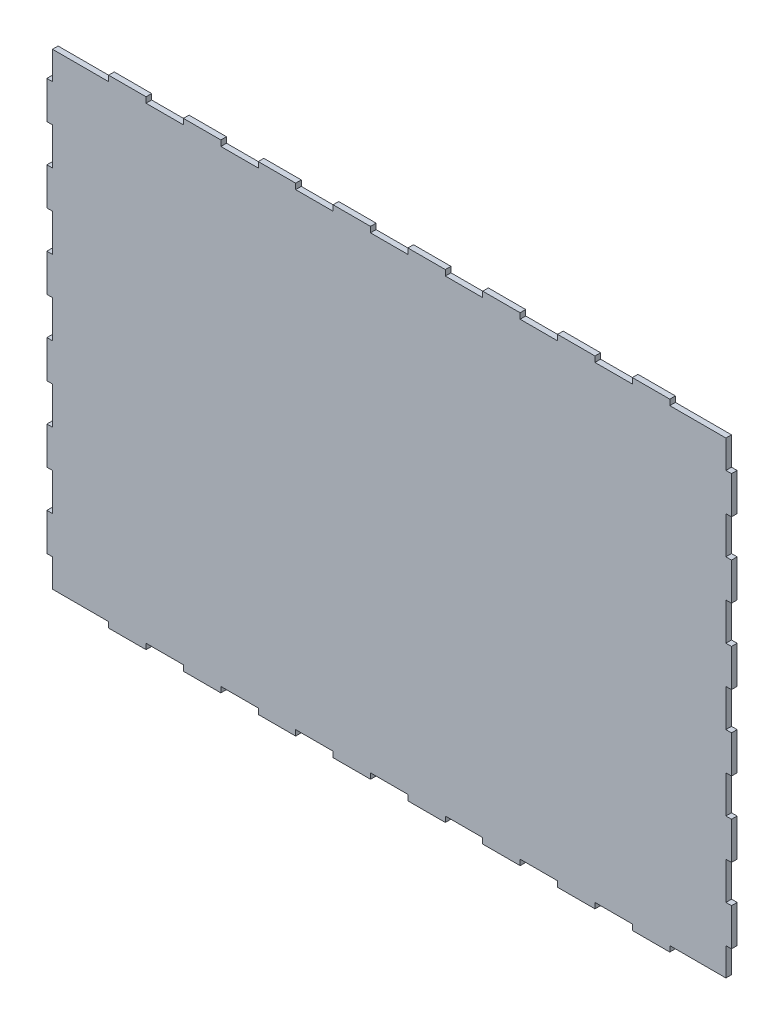
SolidWorks part; units mm, degrees
ref_plane "Front Plane" through (0, 0, 0) normal (0, 0, 1) x (1, 0, 0)
ref_plane "Top Plane" through (0, 0, 0) normal (0, 1, 0) x (1, 0, 0)
ref_plane "Right Plane" through (0, 0, 0) normal (1, 0, 0) x (0, 0, -1)
sketch "Эскиз2" plane through (0, 0, 0) normal (0, 0, 1) x (1, 0, 0)
  line L0 (252.1992, 250.1414) -> (259.9123, 250.1414)
  line L1 (259.9123, 250.1414) -> (259.9123, 254.5354)
  line L2 (259.9123, 254.5354) -> (283.6064, 254.5354)
  line L3 (283.6064, 254.5354) -> (283.6064, 250.1414)
  line L4 (283.6064, 250.1414) -> (305.7717, 250.1414)
  line L5 (305.7717, 250.1414) -> (305.7717, 254.5354)
  line L6 (305.7717, 254.5354) -> (329.4658, 254.5354)
  line L7 (329.4658, 254.5354) -> (329.4658, 250.1414)
  line L8 (329.4658, 250.1414) -> (360.0387, 250.1414)
  line L9 (360.0387, 250.1414) -> (360.0387, 226.7063)
  line L10 (360.0387, 226.7063) -> (365.7711, 226.7063)
  line L11 (365.7711, 226.7063) -> (365.7711, 208.5441)
  line L12 (365.7711, 208.5441) -> (360.0387, 208.5441)
  line L13 (360.0387, 208.5441) -> (360.0387, 191.5536)
  line L14 (360.0387, 191.5536) -> (365.7711, 191.5536)
  line L15 (365.7711, 191.5536) -> (365.7711, 173.3914)
  line L16 (365.7711, 173.3914) -> (360.0387, 173.3914)
  line L17 (360.0387, 173.3914) -> (360.0387, 156.401)
  line L18 (360.0387, 156.401) -> (365.7711, 156.401)
  line L19 (365.7711, 156.401) -> (365.7711, 138.2388)
  line L20 (365.7711, 138.2388) -> (360.0387, 138.2388)
  line L21 (360.0387, 138.2388) -> (360.0387, 121.2484)
  line L22 (360.0387, 121.2484) -> (365.7711, 121.2484)
  line L23 (365.7711, 121.2484) -> (365.7711, 103.0862)
  line L24 (365.7711, 103.0862) -> (360.0387, 103.0862)
  line L25 (360.0387, 103.0862) -> (360.0387, 86.0957)
  line L26 (360.0387, 86.0957) -> (365.7711, 86.0957)
  line L27 (365.7711, 86.0957) -> (365.7711, 67.9335)
  line L28 (365.7711, 67.9335) -> (360.0387, 67.9335)
  line L29 (360.0387, 67.9335) -> (360.0387, 50.9431)
  line L30 (360.0387, 50.9431) -> (365.7711, 50.9431)
  line L31 (365.7711, 50.9431) -> (365.7711, 32.7809)
  line L32 (365.7711, 32.7809) -> (360.0387, 32.7809)
  line L33 (360.0387, 0.0593) -> (328.8776, 0.0593)
  line L34 (328.8776, 0.0593) -> (328.8776, -4.3348)
  line L35 (328.8776, -4.3348) -> (305.1835, -4.3348)
  line L36 (305.1835, -4.3348) -> (305.1835, 0.0593)
  line L37 (305.1835, 0.0593) -> (283.0182, 0.0593)
  line L38 (283.0182, 0.0593) -> (283.0182, -4.3348)
  line L39 (283.0182, -4.3348) -> (259.3241, -4.3348)
  line L40 (259.3241, -4.3348) -> (259.3241, 0.0593)
  line L41 (259.3241, 0.0593) -> (251.611, 0.0593)
  line L42 (251.611, 0.0593) -> (237.1588, 0.0593)
  line L43 (237.1588, 0.0593) -> (237.1588, -4.3348)
  line L44 (237.1588, -4.3348) -> (213.4647, -4.3348)
  line L45 (213.4647, -4.3348) -> (213.4647, 0.0593)
  line L46 (213.4647, 0.0593) -> (191.2994, 0.0593)
  line L47 (191.2994, 0.0593) -> (191.2994, -4.3348)
  line L48 (191.2994, -4.3348) -> (167.6053, -4.3348)
  line L49 (167.6053, -4.3348) -> (167.6053, 0.0593)
  line L50 (167.6053, 0.0593) -> (145.4399, 0.0593)
  line L51 (145.4399, 0.0593) -> (145.4399, -4.3348)
  line L52 (145.4399, -4.3348) -> (121.7459, -4.3348)
  line L53 (121.7459, -4.3348) -> (121.7459, 0.0593)
  line L54 (121.7459, 0.0593) -> (99.5805, 0.0593)
  line L55 (99.5805, 0.0593) -> (99.5805, -4.3348)
  line L56 (99.5805, -4.3348) -> (75.8865, -4.3348)
  line L57 (75.8865, -4.3348) -> (75.8865, 0.0593)
  line L58 (75.8865, 0.0593) -> (53.7211, 0.0593)
  line L59 (53.7211, 0.0593) -> (53.7211, -4.3348)
  line L60 (53.7211, -4.3348) -> (30.0271, -4.3348)
  line L61 (30.0271, -4.3348) -> (30.0271, 0.0593)
  line L62 (30.0271, 0.0593) -> (0.0424, 0.0593)
  line L63 (0.0424, 0.0593) -> (0.0424, 32.7809)
  line L64 (0.0424, 32.7809) -> (-5.6901, 32.7809)
  line L65 (-5.6901, 32.7809) -> (-5.6901, 50.9431)
  line L66 (-5.6901, 50.9431) -> (0.0424, 50.9431)
  line L67 (0.0424, 50.9431) -> (0.0424, 67.9335)
  line L68 (0.0424, 67.9335) -> (-5.6901, 67.9335)
  line L69 (-5.6901, 67.9335) -> (-5.6901, 86.0957)
  line L70 (-5.6901, 86.0957) -> (0.0424, 86.0957)
  line L71 (0.0424, 86.0957) -> (0.0424, 103.0862)
  line L72 (0.0424, 103.0862) -> (-5.6901, 103.0862)
  line L73 (-5.6901, 103.0862) -> (-5.6901, 121.2484)
  line L74 (-5.6901, 121.2484) -> (0.0424, 121.2484)
  line L75 (0.0424, 121.2484) -> (0.0424, 138.2388)
  line L76 (0.0424, 138.2388) -> (-5.6901, 138.2388)
  line L77 (-5.6901, 138.2388) -> (-5.6901, 156.401)
  line L78 (-5.6901, 156.401) -> (0.0424, 156.401)
  line L79 (0.0424, 156.401) -> (0.0424, 173.3914)
  line L80 (0.0424, 173.3914) -> (-5.6901, 173.3914)
  line L81 (-5.6901, 173.3914) -> (-5.6901, 191.5536)
  line L82 (-5.6901, 191.5536) -> (0.0424, 191.5536)
  line L83 (0.0424, 191.5536) -> (0.0424, 208.5441)
  line L84 (0.0424, 208.5441) -> (-5.6901, 208.5441)
  line L85 (-5.6901, 208.5441) -> (-5.6901, 226.7063)
  line L86 (-5.6901, 226.7063) -> (0.0424, 226.7063)
  line L87 (0.0424, 226.7063) -> (0.0424, 250.1414)
  line L88 (0.0424, 250.1414) -> (30.6153, 250.1414)
  line L89 (30.6153, 250.1414) -> (30.6153, 254.5354)
  line L90 (30.6153, 254.5354) -> (54.3093, 254.5354)
  line L91 (54.3093, 254.5354) -> (54.3093, 250.1414)
  line L92 (54.3093, 250.1414) -> (76.4747, 250.1414)
  line L93 (76.4747, 250.1414) -> (76.4747, 254.5354)
  line L94 (76.4747, 254.5354) -> (100.1687, 254.5354)
  line L95 (100.1687, 254.5354) -> (100.1687, 250.1414)
  line L96 (100.1687, 250.1414) -> (122.3341, 250.1414)
  line L97 (122.3341, 250.1414) -> (122.3341, 254.5354)
  line L98 (122.3341, 254.5354) -> (146.0281, 254.5354)
  line L99 (146.0281, 254.5354) -> (146.0281, 250.1414)
  line L100 (146.0281, 250.1414) -> (168.1935, 250.1414)
  line L101 (168.1935, 250.1414) -> (168.1935, 254.5354)
  line L102 (168.1935, 254.5354) -> (191.8876, 254.5354)
  line L103 (191.8876, 254.5354) -> (191.8876, 250.1414)
  line L104 (191.8876, 250.1414) -> (214.0529, 250.1414)
  line L105 (214.0529, 250.1414) -> (214.0529, 254.5354)
  line L106 (214.0529, 254.5354) -> (237.747, 254.5354)
  line L107 (237.747, 254.5354) -> (237.747, 250.1414)
  line L108 (237.747, 250.1414) -> (252.1992, 250.1414)
  line L109 (-2.9475, -11.1911) -> (27.4972, -11.1911)
  line L110 (27.4972, -11.1911) -> (27.4972, -15.5023)
  line L111 (27.4972, -15.5023) -> (51.9003, -15.5023)
  line L112 (51.9003, -15.5023) -> (51.9003, -11.1911)
  line L113 (51.9003, -11.1911) -> (73.3564, -11.1911)
  line L114 (73.3564, -11.1911) -> (73.3564, -15.5023)
  line L115 (73.3564, -15.5023) -> (97.7419, -15.5023)
  line L116 (97.7419, -15.5023) -> (97.7419, -11.1911)
  line L117 (97.7419, -11.1911) -> (119.1409, -11.1911)
  line L118 (119.1409, -11.1911) -> (119.1409, -15.5023)
  line L119 (119.1409, -15.5023) -> (143.6357, -15.5023)
  line L120 (143.6357, -15.5023) -> (143.6357, -11.1911)
  line L121 (143.6357, -11.1911) -> (165.0694, -11.1911)
  line L122 (165.0694, -11.1911) -> (165.0694, -15.5023)
  line L123 (165.0694, -15.5023) -> (189.4359, -15.5023)
  line L124 (189.4359, -15.5023) -> (189.4359, -11.1911)
  line L125 (189.4359, -11.1911) -> (210.8089, -11.1911)
  line L126 (210.8089, -11.1911) -> (210.8089, -15.5023)
  line L127 (210.8089, -15.5023) -> (235.3017, -15.5023)
  line L128 (235.3017, -15.5023) -> (235.3017, -11.1911)
  line L129 (235.3017, -11.1911) -> (256.7496, -11.1911)
  line L130 (256.7496, -11.1911) -> (256.7496, -15.5023)
  line L131 (256.7496, -15.5023) -> (281.117, -15.5023)
  line L132 (281.117, -15.5023) -> (281.117, -11.1911)
  line L133 (281.117, -11.1911) -> (302.5894, -11.1911)
  line L134 (302.5894, -11.1911) -> (302.5894, -15.5023)
  line L135 (302.5894, -15.5023) -> (327.148, -15.5023)
  line L136 (327.148, -15.5023) -> (327.148, -11.1911)
  line L137 (327.148, -11.1911) -> (357.4727, -11.1911)
  line L138 (357.4727, -11.1911) -> (357.4727, -22.8779)
  line L139 (357.4727, -22.8779) -> (365.5155, -22.8779)
  line L140 (365.5155, -22.8779) -> (365.509, -29.7472)
  line L141 (365.509, -29.7472) -> (357.4727, -29.7472)
  line L142 (357.4727, -29.7472) -> (357.4727, -42.673)
  line L143 (357.4727, -42.673) -> (327.148, -42.673)
  line L144 (327.148, -42.673) -> (327.148, -38.9463)
  line L145 (327.148, -38.9463) -> (302.5894, -38.9463)
  line L146 (302.5894, -38.9463) -> (302.5894, -42.673)
  line L147 (302.5894, -42.673) -> (281.117, -42.673)
  line L148 (281.117, -42.673) -> (281.117, -38.9463)
  line L149 (281.117, -38.9463) -> (256.7496, -38.9463)
  line L150 (256.7496, -38.9463) -> (256.7496, -42.673)
  line L151 (256.7496, -42.673) -> (235.3017, -42.673)
  line L152 (235.3017, -42.673) -> (235.3017, -38.9463)
  line L153 (235.3017, -38.9463) -> (210.8089, -38.9463)
  line L154 (210.8089, -38.9463) -> (210.8089, -42.673)
  line L155 (210.8089, -42.673) -> (189.4359, -42.673)
  line L156 (189.4359, -42.673) -> (189.4353, -38.9463)
  line L157 (189.4353, -38.9463) -> (165.0694, -38.9463)
  line L158 (165.0694, -38.9463) -> (165.0694, -42.673)
  line L159 (165.0694, -42.673) -> (143.6357, -42.673)
  line L160 (143.6357, -42.673) -> (143.6357, -38.9463)
  line L161 (143.6357, -38.9463) -> (119.1409, -38.9463)
  line L162 (119.1409, -38.9463) -> (119.1409, -42.673)
  line L163 (119.1409, -42.673) -> (97.7419, -42.673)
  line L164 (97.7419, -42.673) -> (97.7419, -38.9463)
  line L165 (97.7419, -38.9463) -> (73.3564, -38.9463)
  line L166 (73.3564, -38.9463) -> (73.3564, -42.673)
  line L167 (73.3564, -42.673) -> (51.9003, -42.673)
  line L168 (51.9003, -42.673) -> (51.9003, -38.9463)
  line L169 (51.9003, -38.9463) -> (27.4972, -38.9463)
  line L170 (27.4972, -38.9463) -> (27.4972, -42.673)
  line L171 (27.4972, -42.673) -> (-2.9475, -42.673)
  line L172 (-2.9475, -42.673) -> (-2.9475, -29.9471)
  line L173 (-2.9475, -29.9471) -> (-9.6507, -29.9471)
  line L174 (-9.6507, -29.9471) -> (-9.6507, -23.0778)
  line L175 (-9.6507, -23.0778) -> (-2.9475, -23.0778)
  line L176 (-2.9475, -23.0778) -> (-2.9475, -11.1911)
  line L177 (60.6272, -30.2931) -> (60.6272, -23.0367)
  line L178 (60.6272, -23.0367) -> (63.4658, -23.0367)
  line L179 (63.4658, -23.0367) -> (63.4658, -30.2931)
  line L180 (63.4658, -30.2931) -> (60.6272, -30.2931)
  line L181 (30.6174, -30.2532) -> (30.6174, -23.0192)
  line L182 (30.6174, -23.0192) -> (33.456, -23.0192)
  line L183 (33.456, -23.0192) -> (33.456, -30.2532)
  line L184 (33.456, -30.2532) -> (30.6174, -30.2532)
  line L185 (90.633, -30.2432) -> (90.633, -23.0092)
  line L186 (90.633, -23.0092) -> (93.4716, -23.0092)
  line L187 (93.4716, -23.0092) -> (93.4716, -30.2432)
  line L188 (93.4716, -30.2432) -> (90.633, -30.2432)
  line L189 (120.6308, -30.2393) -> (120.6308, -23.0267)
  line L190 (120.6308, -23.0267) -> (123.4694, -23.0267)
  line L191 (123.4694, -23.0267) -> (123.4694, -30.2393)
  line L192 (123.4694, -30.2393) -> (120.6308, -30.2393)
  line L193 (180.6508, -30.1271) -> (180.6508, -23.0192)
  line L194 (180.6508, -23.0192) -> (183.4894, -23.0192)
  line L195 (183.4894, -23.0192) -> (183.4894, -30.1271)
  line L196 (183.4894, -30.1271) -> (180.6508, -30.1271)
  line L197 (153.4727, -23.0191) -> (153.4727, -27.1573)
  line L198 (153.4727, -27.1573) -> (153.4727, -30.1922)
  line L199 (153.4727, -30.1922) -> (150.6341, -30.1922)
  line L200 (150.6341, -30.1922) -> (150.6341, -23.0191)
  line L201 (150.6341, -23.0191) -> (153.4727, -23.0191)
  line L202 (210.6566, -29.9898) -> (210.6566, -23.0192)
  line L203 (210.6566, -23.0192) -> (213.4952, -23.0192)
  line L204 (213.4952, -23.0192) -> (213.4952, -29.9898)
  line L205 (213.4952, -29.9898) -> (210.6566, -29.9898)
  line L206 (244.2529, -30.006) -> (244.2529, -23.0101)
  line L207 (244.2529, -23.0101) -> (247.1018, -23.0101)
  line L208 (247.1018, -23.0101) -> (247.1018, -30.006)
  line L209 (247.1018, -30.006) -> (244.2529, -30.006)
  line L210 (402.371, 242.8158) -> (402.371, 211.9159)
  line L211 (402.371, 211.9159) -> (396.4841, 211.9159)
  line L212 (396.4841, 211.9159) -> (396.4841, 193.3537)
  line L213 (396.4841, 193.3537) -> (402.371, 193.3537)
  line L214 (402.371, 193.3537) -> (402.371, 176.7632)
  line L215 (402.371, 176.7632) -> (396.4841, 176.7632)
  line L216 (396.4841, 176.7632) -> (396.4841, 158.0098)
  line L217 (396.4841, 158.0098) -> (402.371, 158.0098)
  line L218 (402.371, 158.0098) -> (402.371, 141.6106)
  line L219 (402.371, 141.6106) -> (396.4841, 141.6106)
  line L220 (396.4841, 141.6106) -> (396.4841, 123.2484)
  line L221 (396.4841, 123.2484) -> (402.371, 123.2484)
  line L222 (402.371, 123.2484) -> (402.371, 106.458)
  line L223 (402.371, 106.458) -> (396.4841, 106.458)
  line L224 (396.4841, 106.458) -> (396.4841, 87.8958)
  line L225 (396.4841, 87.8958) -> (402.371, 87.8958)
  line L226 (402.371, 87.8958) -> (402.371, 71.3053)
  line L227 (402.371, 71.3053) -> (396.4841, 71.3053)
  line L228 (396.4841, 71.3053) -> (396.4841, 52.9431)
  line L229 (396.4841, 52.9431) -> (402.371, 52.9431)
  line L230 (402.371, 52.9431) -> (402.371, 35.9527)
  line L231 (402.371, 35.9527) -> (396.4841, 35.9527)
  line L232 (396.4841, 35.9527) -> (396.4841, 17.7905)
  line L233 (396.4841, 17.7905) -> (402.371, 17.7905)
  line L234 (402.371, 17.7905) -> (402.371, 8.4645)
  line L235 (402.371, 8.4645) -> (402.371, -22.2271)
  line L236 (402.371, -22.2271) -> (390.3312, -22.2271)
  line L237 (390.3312, -22.2271) -> (390.3312, -14.8105)
  line L238 (390.3312, -14.8105) -> (383.0324, -14.8105)
  line L239 (383.0324, -14.8105) -> (383.0324, -22.2271)
  line L240 (383.0324, -22.2271) -> (370.314, -22.2271)
  line L241 (370.314, 17.7905) -> (376.6791, 17.7905)
  line L242 (376.6791, 17.7905) -> (376.6791, 35.9527)
  line L243 (376.6791, 35.9527) -> (370.314, 35.9527)
  line L244 (370.314, 35.9527) -> (370.314, 52.9431)
  line L245 (370.314, 52.9431) -> (376.6791, 52.9431)
  line L246 (376.6791, 52.9431) -> (376.6791, 71.3053)
  line L247 (376.6791, 71.3053) -> (370.314, 71.3053)
  line L248 (370.314, 71.3053) -> (370.314, 87.8958)
  line L249 (370.314, 87.8958) -> (376.6791, 87.8958)
  line L250 (376.6791, 87.8958) -> (376.6791, 106.458)
  line L251 (376.6791, 106.458) -> (370.314, 106.458)
  line L252 (370.314, 106.458) -> (370.314, 123.2484)
  line L253 (370.314, 123.2484) -> (376.6791, 123.2484)
  line L254 (376.6791, 123.2484) -> (376.6791, 141.6106)
  line L255 (376.6791, 141.6106) -> (370.314, 141.6106)
  line L256 (370.314, 141.6106) -> (370.314, 158.0098)
  line L257 (370.314, 158.0098) -> (376.6791, 158.0098)
  line L258 (376.6791, 158.0098) -> (376.6791, 176.7632)
  line L259 (376.6791, 176.7632) -> (370.314, 176.7632)
  line L260 (370.314, 176.7632) -> (370.314, 193.3537)
  line L261 (370.314, 193.3537) -> (376.6791, 193.3537)
  line L262 (376.6791, 193.3537) -> (376.6791, 211.9159)
  line L263 (376.6791, 211.9159) -> (370.314, 211.9159)
  line L264 (370.314, 211.9159) -> (370.314, 242.8158)
  line L265 (370.314, 242.8158) -> (383.3421, 242.8158)
  line L266 (383.3421, 242.8158) -> (383.3421, 235.2429)
  line L267 (383.3421, 235.2429) -> (390.2615, 235.2429)
  line L268 (390.2615, 235.2429) -> (390.2615, 242.8158)
  line L269 (390.2615, 242.8158) -> (402.371, 242.8158)
  line L270 (382.9975, 171.629) -> (390.2539, 171.629)
  line L271 (390.2539, 171.629) -> (390.2539, 168.7904)
  line L272 (390.2539, 168.7904) -> (382.9975, 168.7904)
  line L273 (382.9975, 168.7904) -> (382.9975, 171.629)
  line L274 (383.0374, 201.6388) -> (390.2714, 201.6388)
  line L275 (390.2714, 201.6388) -> (390.2714, 198.8002)
  line L276 (390.2714, 198.8002) -> (383.0374, 198.8002)
  line L277 (383.0374, 198.8002) -> (383.0374, 201.6388)
  line L278 (383.0474, 141.6232) -> (390.2814, 141.6232)
  line L279 (390.2814, 141.6232) -> (390.2814, 138.7846)
  line L280 (390.2814, 138.7846) -> (383.0474, 138.7846)
  line L281 (383.0474, 138.7846) -> (383.0474, 141.6232)
  line L282 (383.0513, 111.6254) -> (390.2639, 111.6254)
  line L283 (390.2639, 111.6254) -> (390.2639, 108.7868)
  line L284 (390.2639, 108.7868) -> (383.0513, 108.7868)
  line L285 (383.0513, 108.7868) -> (383.0513, 111.6254)
  line L286 (383.1635, 51.6054) -> (390.2714, 51.6054)
  line L287 (390.2714, 51.6054) -> (390.2714, 48.7668)
  line L288 (390.2714, 48.7668) -> (383.1635, 48.7668)
  line L289 (383.1635, 48.7668) -> (383.1635, 51.6054)
  line L290 (390.2715, 78.7835) -> (386.1333, 78.7835)
  line L291 (386.1333, 78.7835) -> (383.0984, 78.7835)
  line L292 (383.0984, 78.7835) -> (383.0984, 81.6221)
  line L293 (383.0984, 81.6221) -> (390.2715, 81.6221)
  line L294 (390.2715, 81.6221) -> (390.2715, 78.7835)
  line L295 (383.3008, 21.5996) -> (390.2714, 21.5996)
  line L296 (390.2714, 21.5996) -> (390.2714, 18.761)
  line L297 (390.2714, 18.761) -> (383.3008, 18.761)
  line L298 (383.3008, 18.761) -> (383.3008, 21.5996)
  spline S0 degree 3 poles (360.0387, 32.7809) (360.0387, 6.279) (360.0387, 29.9698) (360.0387, 0.0593) knots 0.3 0.3 0.3 0.3 0.309091 0.309091 0.309091 0.309091
  spline S1 degree 3 poles (370.314, -22.2271) (370.314, -8.8879) (370.314, 4.4513) (370.314, 17.7905) knots 0.508197 0.508197 0.508197 0.508197 0.52459 0.52459 0.52459 0.52459
sketch "Sketch2" plane through (0, 0, 0) normal (0, 0, 1) x (1, 0, 0)
  line L0 (-2.9576, 75.0592) -> (0.0424, 75.0592)
  line L1 (0.0424, 250.0592) -> (30.0424, 250.0592)
  line L2 (0.0424, 250.0592) -> (0.0424, 235.0592)
  line L5 (-2.9576, 35.0592) -> (0.0424, 35.0592)
  line L6 (-2.9576, 35.0592) -> (-2.9576, 15.0592)
  line L7 (-2.9576, 15.0592) -> (0.0424, 15.0592)
  line L10 (-2.9576, 55.0592) -> (0.0424, 55.0592)
  line L11 (-2.9576, 75.0592) -> (-2.9576, 55.0592)
  line L12 (-2.9576, 115.0592) -> (0.0424, 115.0592)
  line L14 (-2.9576, 95.0592) -> (0.0424, 95.0592)
  line L15 (-2.9576, 115.0592) -> (-2.9576, 95.0592)
  line L16 (-2.9576, 155.0592) -> (0.0424, 155.0592)
  line L18 (-2.9576, 135.0592) -> (0.0424, 135.0592)
  line L19 (-2.9576, 155.0592) -> (-2.9576, 135.0592)
  line L20 (-2.9576, 195.0592) -> (0.0424, 195.0592)
  line L22 (-2.9576, 175.0592) -> (0.0424, 175.0592)
  line L23 (-2.9576, 195.0592) -> (-2.9576, 175.0592)
  line L24 (-2.9576, 235.0592) -> (0.0424, 235.0592)
  line L26 (-2.9576, 215.0592) -> (0.0424, 215.0592)
  line L27 (-2.9576, 235.0592) -> (-2.9576, 215.0592)
  line L28 (70.0424, 250.0592) -> (70.0424, 253.0592)
  line L30 (30.0424, 250.0592) -> (30.0424, 253.0592)
  line L31 (30.0424, 253.0592) -> (50.0424, 253.0592)
  line L32 (50.0424, 250.0592) -> (50.0424, 253.0592)
  line L34 (90.0424, 250.0592) -> (90.0424, 253.0592)
  line L35 (70.0424, 253.0592) -> (90.0424, 253.0592)
  line L36 (110.0424, 250.0592) -> (110.0424, 253.0592)
  line L38 (130.0424, 250.0592) -> (130.0424, 253.0592)
  line L39 (110.0424, 253.0592) -> (130.0424, 253.0592)
  line L40 (150.0424, 250.0592) -> (150.0424, 253.0592)
  line L42 (170.0424, 250.0592) -> (170.0424, 253.0592)
  line L43 (150.0424, 253.0592) -> (170.0424, 253.0592)
  line L44 (190.0424, 250.0592) -> (190.0424, 253.0592)
  line L46 (210.0424, 250.0592) -> (210.0424, 253.0592)
  line L47 (190.0424, 253.0592) -> (210.0424, 253.0592)
  line L48 (230.0424, 250.0592) -> (230.0424, 253.0592)
  line L50 (250.0424, 250.0592) -> (250.0424, 253.0592)
  line L51 (230.0424, 253.0592) -> (250.0424, 253.0592)
  line L52 (270.0424, 250.0592) -> (270.0424, 253.0592)
  line L54 (290.0424, 250.0592) -> (290.0424, 253.0592)
  line L55 (270.0424, 253.0592) -> (290.0424, 253.0592)
  line L56 (310.0424, 250.0592) -> (310.0424, 253.0592)
  line L58 (330.0424, 250.0592) -> (330.0424, 253.0592)
  line L59 (310.0424, 253.0592) -> (330.0424, 253.0592)
  line L60 (360.0424, 125.0592) -> (20.2768, 125.0592) construction
  line L61 (180.0424, 0.0592) -> (180.0424, 110.7569) construction
  line L118 (330.0424, 0.0592) -> (360.0424, 0.0592)
  line L119 (90.0424, 250.0592) -> (110.0424, 250.0592)
  line L120 (0.0424, 0.0592) -> (30.0424, 0.0592)
  line L121 (290.0424, 0.0592) -> (310.0424, 0.0592)
  line L122 (170.0424, 250.0592) -> (190.0424, 250.0592)
  line L123 (130.0424, 250.0592) -> (150.0424, 250.0592)
  line L124 (250.0424, 0.0592) -> (270.0424, 0.0592)
  line L125 (50.0424, 250.0592) -> (70.0424, 250.0592)
  line L126 (210.0424, 250.0592) -> (230.0424, 250.0592)
  line L127 (250.0424, 250.0592) -> (270.0424, 250.0592)
  line L128 (290.0424, 250.0592) -> (310.0424, 250.0592)
  line L129 (330.0424, 250.0592) -> (360.0424, 250.0592)
  line L130 (0.0424, 215.0592) -> (0.0424, 195.0592)
  line L131 (210.0424, 0.0592) -> (230.0424, 0.0592)
  line L132 (50.0424, 0.0592) -> (70.0424, 0.0592)
  line L133 (0.0424, 175.0592) -> (0.0424, 155.0592)
  line L134 (130.0424, 0.0592) -> (150.0424, 0.0592)
  line L135 (0.0424, 135.0592) -> (0.0424, 115.0592)
  line L136 (170.0424, 0.0592) -> (190.0424, 0.0592)
  line L137 (0.0424, 95.0592) -> (0.0424, 75.0592)
  line L138 (90.0424, 0.0592) -> (110.0424, 0.0592)
  line L139 (0.0424, 55.0592) -> (0.0424, 35.0592)
  line L140 (0.0424, 15.0592) -> (0.0424, 0.0592)
  line L141 (310.0424, -2.9408) -> (330.0424, -2.9408)
  line L142 (330.0424, 0.0592) -> (330.0424, -2.9408)
  line L143 (310.0424, 0.0592) -> (310.0424, -2.9408)
  line L144 (270.0424, -2.9408) -> (290.0424, -2.9408)
  line L145 (290.0424, 0.0592) -> (290.0424, -2.9408)
  line L146 (270.0424, 0.0592) -> (270.0424, -2.9408)
  line L147 (230.0424, -2.9408) -> (250.0424, -2.9408)
  line L148 (250.0424, 0.0592) -> (250.0424, -2.9408)
  line L149 (230.0424, 0.0592) -> (230.0424, -2.9408)
  line L150 (190.0424, -2.9408) -> (210.0424, -2.9408)
  line L151 (210.0424, 0.0592) -> (210.0424, -2.9408)
  line L152 (190.0424, 0.0592) -> (190.0424, -2.9408)
  line L153 (150.0424, -2.9408) -> (170.0424, -2.9408)
  line L154 (170.0424, 0.0592) -> (170.0424, -2.9408)
  line L155 (150.0424, 0.0592) -> (150.0424, -2.9408)
  line L156 (110.0424, -2.9408) -> (130.0424, -2.9408)
  line L157 (130.0424, 0.0592) -> (130.0424, -2.9408)
  line L158 (110.0424, 0.0592) -> (110.0424, -2.9408)
  line L159 (70.0424, -2.9408) -> (90.0424, -2.9408)
  line L160 (90.0424, 0.0592) -> (90.0424, -2.9408)
  line L161 (50.0424, 0.0592) -> (50.0424, -2.9408)
  line L162 (30.0424, -2.9408) -> (50.0424, -2.9408)
  line L163 (30.0424, 0.0592) -> (30.0424, -2.9408)
  line L164 (70.0424, 0.0592) -> (70.0424, -2.9408)
  line L165 (360.0424, 250.0592) -> (360.0424, 235.0592)
  line L166 (360.0424, 15.0592) -> (360.0424, 0.0592)
  line L167 (360.0424, 55.0592) -> (360.0424, 35.0592)
  line L168 (360.0424, 95.0592) -> (360.0424, 75.0592)
  line L169 (360.0424, 135.0592) -> (360.0424, 115.0592)
  line L170 (360.0424, 175.0592) -> (360.0424, 155.0592)
  line L171 (360.0424, 215.0592) -> (360.0424, 195.0592)
  line L172 (363.0424, 235.0592) -> (363.0424, 215.0592)
  line L173 (363.0424, 215.0592) -> (360.0424, 215.0592)
  line L174 (363.0424, 235.0592) -> (360.0424, 235.0592)
  line L175 (363.0424, 195.0592) -> (363.0424, 175.0592)
  line L176 (363.0424, 175.0592) -> (360.0424, 175.0592)
  line L177 (363.0424, 195.0592) -> (360.0424, 195.0592)
  line L178 (363.0424, 155.0592) -> (363.0424, 135.0592)
  line L179 (363.0424, 135.0592) -> (360.0424, 135.0592)
  line L180 (363.0424, 155.0592) -> (360.0424, 155.0592)
  line L181 (363.0424, 115.0592) -> (363.0424, 95.0592)
  line L182 (363.0424, 95.0592) -> (360.0424, 95.0592)
  line L183 (363.0424, 115.0592) -> (360.0424, 115.0592)
  line L184 (363.0424, 75.0592) -> (363.0424, 55.0592)
  line L185 (363.0424, 55.0592) -> (360.0424, 55.0592)
  line L186 (363.0424, 15.0592) -> (360.0424, 15.0592)
  line L187 (363.0424, 35.0592) -> (363.0424, 15.0592)
  line L188 (363.0424, 35.0592) -> (360.0424, 35.0592)
  line L189 (363.0424, 75.0592) -> (360.0424, 75.0592)
  point P7 (30.0424, 250.0592)
  point P14 (0.0424, 15.0592)
  point P98 (30.0424, 0.0592)
  point P124 (360.0424, 15.0592)
  dimension "D1" = 250
  dimension "D2" = 360
  dimension "D3" = 20
  dimension "D4" = 3
  dimension "D5" = 15
  dimension "D6" = 6
  dimension "D7" = 30
  dimension "D8" = 20
  dimension "D9" = 3
  dimension "D11" = 20
  dimension "D12" = 20
  dimension "D10" = 8
extrude "Boss-Extrude1" add sketch "Sketch2" along normal blind 3
